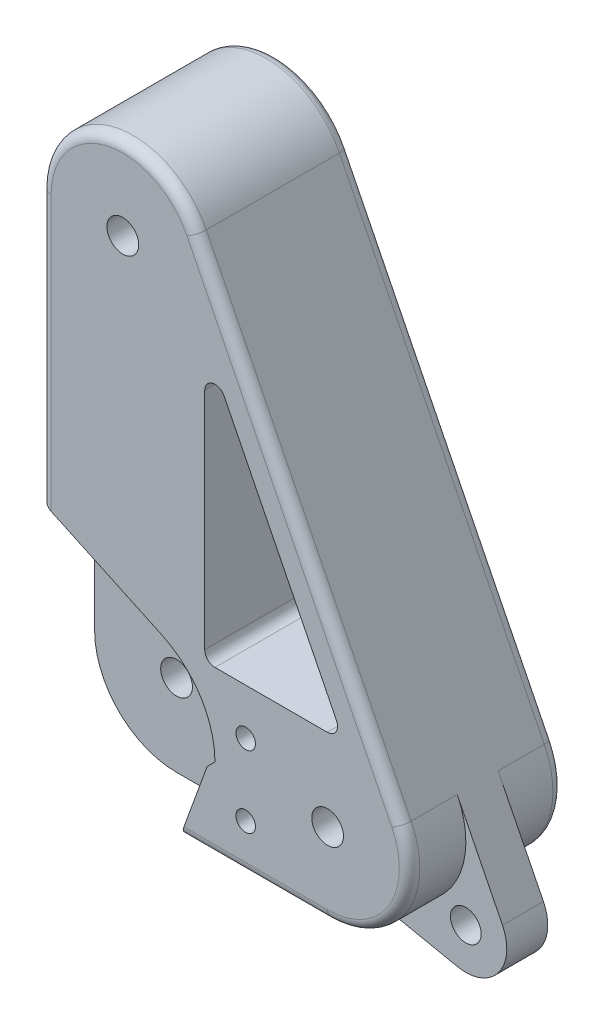
SolidWorks part; units mm, degrees
ref_plane "Front Plane" through (0, 0, 0) normal (0, 0, 1) x (1, 0, 0)
ref_plane "Top Plane" through (0, 0, 0) normal (0, 1, 0) x (1, 0, 0)
ref_plane "Right Plane" through (0, 0, 0) normal (1, 0, 0) x (0, 0, -1)
sketch "Sketch1" plane through (0, 0, 0) normal (0, 0, 1) x (1, 0, 0)
  line L2 (20, -8) -> (0, -8)
  line L3 (-8, 40) -> (-8, 0)
  line L4 (7.1554, 43.5777) -> (27.1554, 3.5777)
  circle A0 centre (0, 0) radius 1.55
  circle A1 centre (20, 0) radius 1.55
  circle A2 centre (0, 40) radius 1.55
  arc A3 (-8, 40) -> (7.1554, 43.5777) centre (0, 40) cw
  arc A4 (-8, 0) -> (0, -8) centre (0, 0) ccw
  arc A5 (27.1554, 3.5777) -> (20, -8) centre (20, 0) cw
  dimension "D1" = 3.1
  dimension "D2" = 8
  dimension "D3" = 40
  dimension "D5" = 20
extrude "Boss-Extrude1" add sketch "Sketch1" along normal blind 15
fillet "Fillet1" radius 1 6 edges at (26.8052, -4.2058, 0) (10, -8, 0) (-5.6569, -5.6569, 0) (-8, 20, 0) (-1.838, 47.786, 0) (17.1554, 23.5777, 0)
fillet "Fillet2" radius 1 6 edges at (-8, 20, 15) (-5.6569, -5.6569, 15) (10, -8, 15) (26.8052, -4.2058, 15) (-1.838, 47.786, 15) (17.1554, 23.5777, 15)
sketch "Sketch2" plane through (0, 0, 15) normal (0, 0, 1) x (1, 0, 0)
  line L2 (5.6017, -8) -> (-8, -8)
  line L3 (-8, -8) -> (-8, 13.6609)
  line L4 (-8, 13.6609) -> (3.8036, 8.1568)
  line L5 (9, 0) -> (5.6017, -8) construction
  line L6 (5.6017, -8) -> (8.235, -0.765)
  line L7 (8.235, -0.765) -> (9, 0)
  line L8 (20, -8) -> (0, -8) construction
  line L9 (-8, 0) -> (-8, 40) construction
  circle A2 centre (0, 0) radius 1.55 construction
  arc A3 (3.8036, 8.1568) -> (9, 0) centre (0, 0) cw
  dimension "D1" = 9
  dimension "D2" = 8
  dimension "D3" = 25
  dimension "D4" = 45
  dimension "D5" = 20
extrude "Cut-Extrude1" cut sketch "Sketch2" against normal blind 5.25
ref_plane "Plane1" through (0, 0, 7.5) normal (0, 0, 1) x (1, 0, 0)
mirror "Mirror1" about plane through (0, 0, 7.5) normal (0, 0, 1) of "Cut-Extrude1"
sketch "Sketch3" plane through (0, 0, 7.5) normal (0, 0, 1) x (1, 0, 0)
  line L0 (31.5745, -5.2605) -> (27.1554, 3.5777)
  line L1 (27.1554, 3.5777) -> (12.8008, -8)
  line L2 (7.1554, 43.5777) -> (27.1554, 3.5777) construction
  line L3 (12.8008, -8) -> (27.189, -10.9669)
  line L5 (20, -8) -> (5.6017, -8) construction
  circle A0 centre (27.9968, -7.0493) radius 1.5
  arc A1 (27.189, -10.9669) -> (31.5745, -5.2605) centre (27.9968, -7.0493) ccw
  dimension "D1" = 3
  dimension "D2" = 4
extrude "Boss-Extrude2" add sketch "Sketch3" against normal blind 2 and the other way blind 2
sketch "Sketch4" plane through (0, 0, 0) normal (0, 0, -1) x (-1, 0, 0)
  line L0 (0, 0) -> (-15.2179, 0) construction
  circle A0 centre (-12, 3.5) radius 0.95
  circle A2 centre (-12, -3.5) radius 0.95
  circle A3 centre (0, 0) radius 1.55 construction
  dimension "D1" = 1.9
  dimension "D2" = 7
  dimension "D3" = 12
extrude "Cut-Extrude2" cut sketch "Sketch4" against normal through all
sketch "Sketch5" plane through (0, 0, 0) normal (0, 0, -1) x (-1, 0, 0)
  line L0 (-8, 35.1803) -> (-8, 8)
  line L3 (-8, 8) -> (-20, 8)
  line L4 (-21.6793, 7.8218) -> (-8, 35.1803)
  line L5 (8, 40) -> (8, 13.6609) construction
  line L6 (-27.1554, 3.5777) -> (-7.1554, 43.5777) construction
  arc A3 (-21.6793, 7.8218) -> (-20, 8) centre (-20, 0) cw
  circle A4 centre (0, 0) radius 1.55 construction
  dimension "D4" = 8
  dimension "D1" = 16
  dimension "D2" = 3
  dimension "D5" = 8
extrude "Cut-Extrude3" cut sketch "Sketch5" against normal through all
fillet "Fillet3" radius 1 3 edges at (8, 35.1803, 7.5) (8, 8, 7.5) (21.6793, 7.8218, 7.5)
